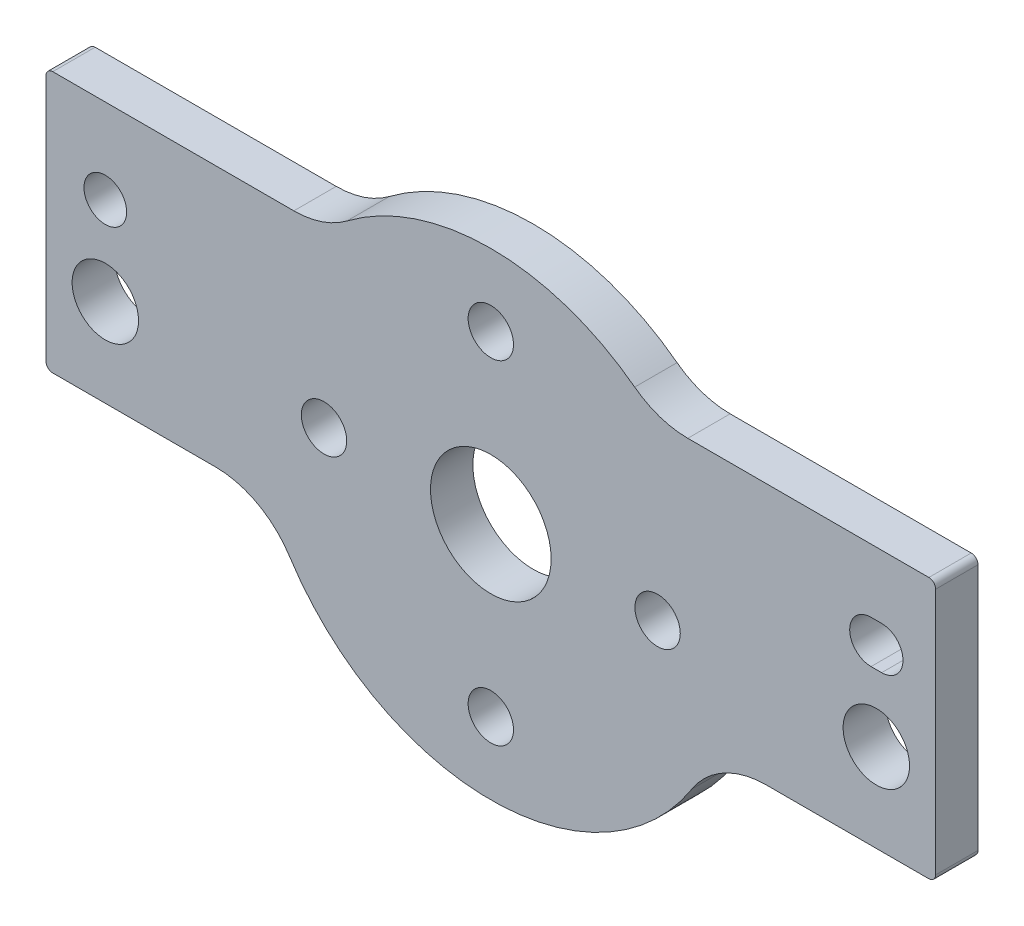
SolidWorks part; units mm, degrees
ref_plane "Front Plane" through (0, 0, 0) normal (0, 0, 1) x (1, 0, 0)
ref_plane "Top Plane" through (0, 0, 0) normal (0, 1, 0) x (1, 0, 0)
ref_plane "Right Plane" through (0, 0, 0) normal (1, 0, 0) x (0, 0, -1)
sketch "Sketch1" plane through (0, 0, 0) normal (0, 0, 1) x (1, 0, 0)
  line L1 (33.3375, 6.604) -> (-33.3375, 6.604)
  line L2 (33.3375, 6.604) -> (33.3375, -6.604)
  line L3 (33.3375, -6.604) -> (-33.3375, -6.604)
  line L4 (-33.3375, 6.604) -> (-33.3375, -6.604)
  line L5 (33.3375, 6.604) -> (-33.3375, -6.604) construction
  line L6 (33.3375, -6.604) -> (-33.3375, 6.604) construction
  point P0 (0, 0)
  dimension "D1" = 66.675
  dimension "D2" = 13.208
extrude "Boss-Extrude1" add sketch "Sketch1" along normal blind 3.175
sketch "Sketch2" plane through (0, 0, 3.175) normal (0, 0, 1) x (1, 0, 0)
  circle A0 centre (0, 0) radius 17.9
  dimension "D1" = 35.8
extrude "Boss-Extrude2" add sketch "Sketch2" against normal through all
sketch "Sketch8" plane through (0, 0, 3.175) normal (0, 0, 1) x (1, 0, 0)
  line L0 (-33.3375, 6.604) -> (-33.3375, -6.604) construction
  line L1 (33.3375, 6.604) -> (-33.3375, 6.604)
  line L2 (33.3375, 6.604) -> (33.3375, 12.954)
  line L3 (33.3375, 12.954) -> (-33.3375, 12.954)
  line L4 (-33.3375, 6.604) -> (-33.3375, 12.954)
  line L5 (16.6372, -6.604) -> (33.3375, -6.604) construction
  dimension "D1" = 19.558
extrude "Boss-Extrude3" add sketch "Sketch8" against normal through all
fillet "Fillet1" radius 6.604 4 edges at (-16.6372, -6.604, 1.5875) (16.6372, -6.604, 1.5875) (-12.3533, 12.954, 1.5875) (12.3533, 12.954, 1.5875)
fillet "Fillet2" radius 0.508 4 edges at (33.3375, -6.604, 1.5875) (-33.3375, -6.604, 1.5875) (33.3375, 12.954, 1.5875) (-33.3375, 12.954, 1.5875)
hole_wizard "#10 Clearance Hole1" positions "Sketch3" profile "Sketch4" hole size "#10" standard "ANSI Inch" end condition through all
sketch "Sketch3" plane through (0, 0, 3.175) normal (0, 0, 1) x (1, 0, 0)
  line L0 (0, 0) -> (0, 50000) construction
  point P0 (28.8925, 0)
  point P7 (-28.8925, 0)
  dimension "D1" = 57.785
sketch "Sketch4" plane through (28.8925, 0, 3.175) normal (1, 0, 0) x (0, -1, 0)
  line L0 (0, 0) -> (0, 3.175)
  line L1 (0, 3.175) -> (2.4892, 3.175)
  line L2 (2.4892, 3.175) -> (2.4892, 0)
  line L5 (2.4892, 0) -> (0, 0)
  line L11 (0, -6.35) -> (0, 107.95) construction
  dimension "Thru Hole Dia." = 4.9784
  dimension "Thru Hole Depth" = 3.175
sketch "Sketch5" plane through (0, 0, 3.175) normal (0, 0, 1) x (1, 0, 0)
  circle A0 centre (0, 0) radius 4.5212
  dimension "D1" = 9.0424
extrude "Cut-Extrude1" cut sketch "Sketch5" against normal through all
hole_wizard "M3 Clearance Hole1" positions "Sketch6" profile "Sketch7" hole size "M3" standard "ANSI Metric" end condition through all
sketch "Sketch6" plane through (0, 0, 3.175) normal (0, 0, 1) x (1, 0, 0)
  circle A0 centre (0, 0) radius 12.5
  point P0 (0, 12.5)
  point P8 (-12.5, 0)
  point P10 (0, -12.5)
  point P12 (12.5, 0)
  dimension "D1" = 25
sketch "Sketch7" plane through (0, 12.5, 3.175) normal (1, 0, 0) x (0, -1, 0)
  line L0 (0, 0) -> (0, 3.175)
  line L1 (0, 3.175) -> (1.7, 3.175)
  line L2 (1.7, 3.175) -> (1.7, 0)
  line L5 (1.7, 0) -> (0, 0)
  line L11 (0, -6.35) -> (0, 107.95) construction
  dimension "Thru Hole Dia." = 3.4
  dimension "Thru Hole Depth" = 3.175
sketch "Sketch9" plane through (0, 0, 3.175) normal (0, 0, 1) x (1, 0, 0)
  line L0 (0, 0) -> (0, 50000) construction
  line L1 (-28.8925, 0) -> (-28.8925, 50000) construction
  line L2 (-14.7625, 12.954) -> (-32.8295, 12.954) construction
  line L3 (28.4956, 6.604) -> (29.2894, 6.604) construction
  line L4 (28.4956, 8.2042) -> (29.2894, 8.2042)
  line L5 (28.4956, 5.0038) -> (29.2894, 5.0038)
  circle A0 centre (-28.8925, 6.604) radius 1.6002
  circle A1 centre (28.8925, 6.604) radius 1.6002 construction
  arc A2 (28.4956, 8.2042) -> (28.4956, 5.0038) centre (28.4956, 6.604) ccw
  arc A3 (29.2894, 5.0038) -> (29.2894, 8.2042) centre (29.2894, 6.604) ccw
  point P14 (28.8925, 6.604)
  dimension "D1" = 6.35
  dimension "D2" = 3.2004
  dimension "D3" = 0.7937
extrude "Cut-Extrude2" cut sketch "Sketch9" against normal through all
